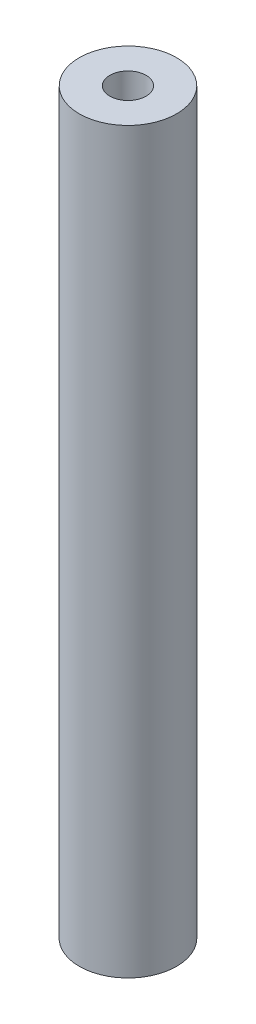
SolidWorks part; units mm, degrees
ref_plane "Front Plane" through (0, 0, 0) normal (0, 0, 1) x (1, 0, 0)
ref_plane "Top Plane" through (0, 0, 0) normal (0, 1, 0) x (1, 0, 0)
ref_plane "Right Plane" through (0, 0, 0) normal (1, 0, 0) x (0, 0, -1)
sketch "Sketch1" plane through (0, 0, 0) normal (0, 1, 0) x (1, 0, 0)
  circle A0 centre (0, 0) radius 7.25
  dimension "D1" = 14.5
extrude "Boss-Extrude1" add sketch "Sketch1" along normal blind 110
sketch "Sketch2" plane through (0, 110, 0) normal (0, 1, 0) x (1, 0, 0)
  circle A0 centre (0, 0) radius 2.7
extrude "Cut-Extrude1" cut sketch "Sketch2" against normal blind 110
